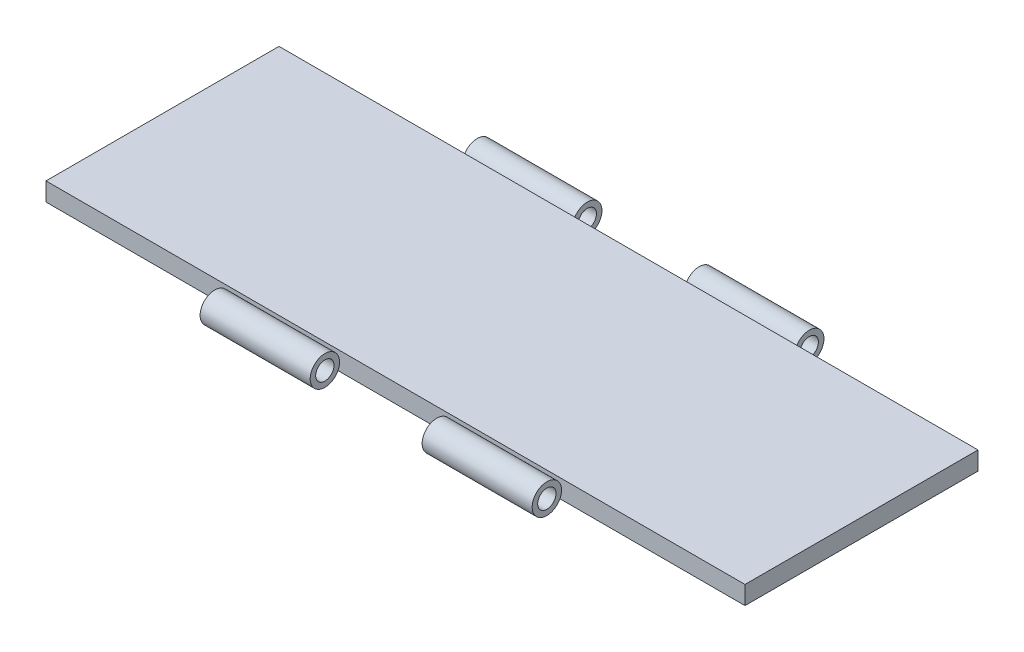
SolidWorks part; units mm, degrees
ref_plane "Alzado" through (0, 0, 0) normal (0, 0, 1) x (1, 0, 0)
ref_plane "Planta" through (0, 0, 0) normal (0, 1, 0) x (1, 0, 0)
ref_plane "Vista lateral" through (0, 0, 0) normal (1, 0, 0) x (0, 0, -1)
sketch "Croquis1" plane through (0, 0, 0) normal (0, 1, 0) x (1, 0, 0)
  line L1 (-38.1, -12.7) -> (38.1, -12.7)
  line L2 (-38.1, -12.7) -> (-38.1, 12.7)
  line L3 (-38.1, 12.7) -> (38.1, 12.7)
  line L4 (38.1, -12.7) -> (38.1, 12.7)
  line L5 (-38.1, -12.7) -> (38.1, 12.7) construction
  line L6 (-38.1, 12.7) -> (38.1, -12.7) construction
  point P0 (0, 0)
  dimension "D1" = 76.2
  dimension "D2" = 25.4
extrude "Saliente-Extruir1" add sketch "Croquis1" along normal blind 2
sketch "Croquis2" plane through (-38.1, 0, 0) normal (-1, 0, 0) x (0, 0, 1)
  line L0 (12.7, 2) -> (12.7, 0) construction
  circle A0 centre (-14.3062, 0.901) radius 1.6
  circle A1 centre (14.3, 0.901) radius 1.6
  dimension "D1" = 3.2
  dimension "D2" = 1.6
  dimension "D3" = 3.2
extrude "Saliente-Extruir2" add sketch "Croquis2" against normal up to surface (76.2 mm away) separate body up to face at (38.1, 1, 0)
sketch "Croquis4" plane through (-38.1, 0, 0) normal (-1, 0, 0) x (0, 0, 1)
  circle A0 centre (-14.3062, 0.901) radius 1
  circle A1 centre (14.3, 0.901) radius 1
extrude "Cortar-Extruir2" cut sketch "Croquis4" against normal up to surface (76.2 mm away) up to face at (38.1, 0.901, -12.7062)
sketch "Croquis5" plane through (0, 2, 0) normal (0, 1, 0) x (1, 0, 0)
  line L0 (-38.1, 14.3062) -> (-18.1, 14.3062)
  line L1 (-38.1, 15.9062) -> (-38.1, 12.7062) construction
  line L2 (38.1, 14.3062) -> (18.1, 14.3062)
  line L3 (38.1, 12.7062) -> (38.1, 15.9062) construction
  line L4 (-18.1, 14.3062) -> (-6.1, 14.3062)
  line L5 (18.1, 14.3062) -> (6.1, 14.3062)
  line L7 (38.1, 12.7) -> (-38.1, 12.7) construction
  line L8 (-38.1, 15.9124) -> (-18.1, 15.9124)
  line L9 (-38.1, 15.9124) -> (-38.1, 12.7)
  line L10 (-38.1, 12.7) -> (-18.1, 12.7)
  line L11 (-18.1, 15.9124) -> (-18.1, 12.7)
  line L12 (-38.1, 15.9124) -> (-18.1, 12.7) construction
  line L14 (-38.1, 12.7) -> (-18.1, 15.9124) construction
  line L16 (-38.1, -15.9) -> (38.1, -15.9) construction
  line L17 (18.1, 12.7062) -> (38.1, 12.7062)
  line L18 (18.1, 12.7062) -> (18.1, 15.9062)
  line L19 (18.1, 15.9062) -> (38.1, 15.9062)
  line L20 (38.1, 12.7062) -> (38.1, 15.9062)
  line L21 (18.1, 12.7062) -> (38.1, 15.9062) construction
  line L22 (18.1, 15.9062) -> (38.1, 12.7062) construction
  line L23 (-6.1, 12.7062) -> (6.1, 12.7062)
  line L24 (-6.1, 12.7062) -> (-6.1, 15.9062)
  line L25 (-6.1, 15.9062) -> (6.1, 15.9062)
  line L26 (6.1, 12.7062) -> (6.1, 15.9062)
  line L27 (-6.1, 12.7062) -> (6.1, 15.9062) construction
  line L28 (-6.1, 15.9062) -> (6.1, 12.7062) construction
  line L32 (-38.1, -12.7) -> (38.1, -12.7) construction
  line L33 (-38.1, -15.9) -> (-18.1, -15.9)
  line L34 (-38.1, -15.9) -> (-38.1, -12.7)
  line L35 (-38.1, -12.7) -> (-18.1, -12.7)
  line L36 (-18.1, -15.9) -> (-18.1, -12.7)
  line L37 (-38.1, -15.9) -> (-18.1, -12.7) construction
  line L38 (-38.1, -12.7) -> (-18.1, -15.9) construction
  line L40 (-6.1, -15.9) -> (6.1, -15.9)
  line L41 (-6.1, -15.9) -> (-6.1, -12.7)
  line L42 (-6.1, -12.7) -> (6.1, -12.7)
  line L43 (6.1, -15.9) -> (6.1, -12.7)
  line L44 (-6.1, -15.9) -> (6.1, -12.7) construction
  line L45 (-6.1, -12.7) -> (6.1, -15.9) construction
  line L46 (18.1, -15.9) -> (38.1, -15.9)
  line L47 (18.1, -15.9) -> (18.1, -12.7)
  line L48 (18.1, -12.7) -> (38.1, -12.7)
  line L49 (38.1, -15.9) -> (38.1, -12.7)
  line L50 (18.1, -15.9) -> (38.1, -12.7) construction
  line L51 (18.1, -12.7) -> (38.1, -15.9) construction
  point P8 (-12.1, 14.3062)
  point P11 (-28.1, 14.3062)
  point P17 (12.1, 14.3062)
  point P19 (28.1, 14.3062)
  point P20 (28.1, 14.3062)
  point P25 (0, 14.3062)
  point P36 (-28.1, -14.3)
  point P47 (0, -14.3)
  point P50 (28.1, -14.3)
  dimension "D1" = 20
  dimension "D2" = 12
  dimension "D3" = 12
  dimension "D4" = 20
extrude "Cortar-Extruir6" cut sketch "Croquis5" against normal through all and the other way through all contours L10 L11 L8 L9 | L23 L26 L25 L24 | L17 L20 L19 L18 | L40 L43 L42 L41 | L33 L36 L35 L34 | L46 L49 L48 L47
